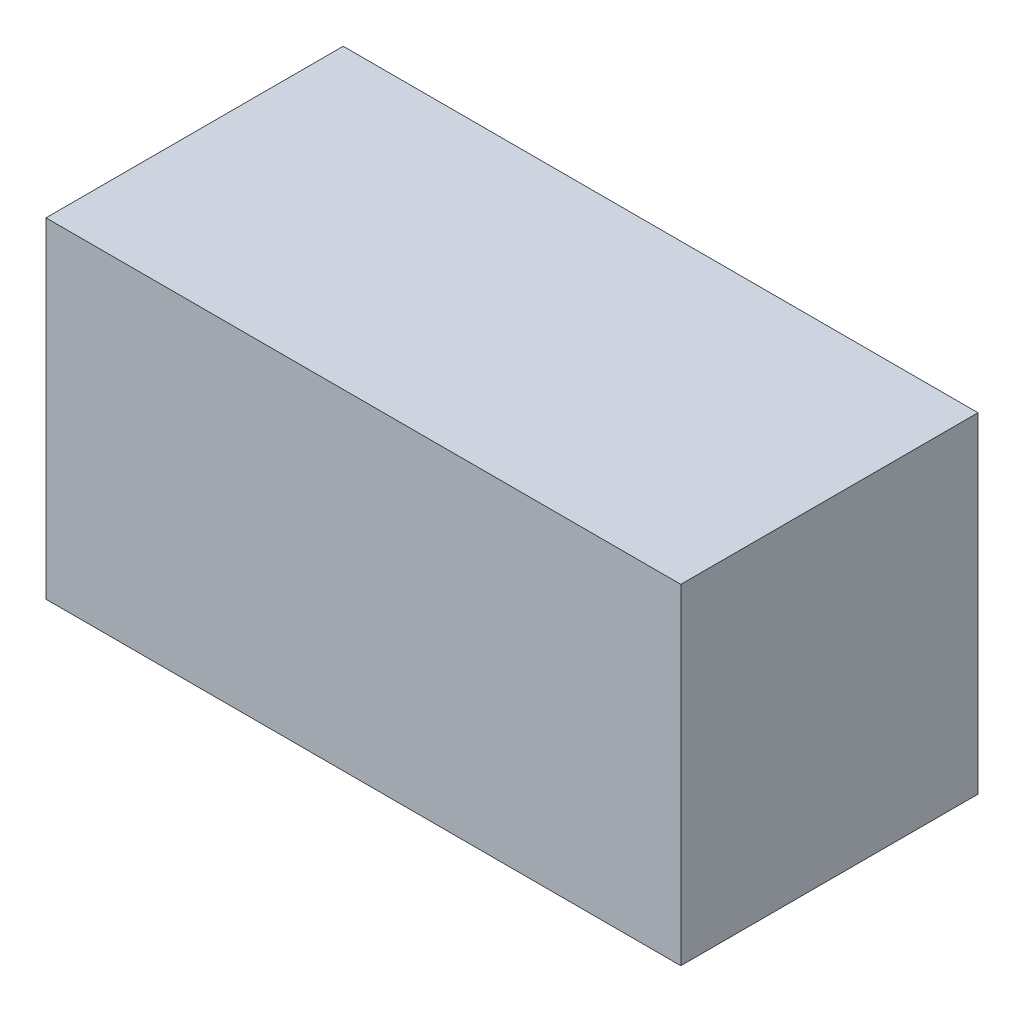
SolidWorks part; units mm, degrees
other "A"
other "B"
other "corpo 3"
other "C" parameters "Espessura"=2
material "AISI 1020"
ref_plane "Plano superior" through (0, 0, 0) normal (0, 0, 1) x (1, 0, 0)
ref_plane "Plano frontal" through (0, 0, 0) normal (0, 1, 0) x (1, 0, 0)
ref_plane "Plano direito" through (0, 0, 0) normal (1, 0, 0) x (0, 0, -1)
other "CAIXA"
ref_plane "Default Plane" through (78.1989, -63.755, 60) normal (0, 1, 0) x (1, 0, 0)
ref_plane "TOP" through (0, 0, 0) normal (0, 0, 1) x (1, 0, 0)
sketch "Esboço1" plane through (0, 0, 0) normal (0, 0, 1) x (1, 0, 0)
  line L1 (-78.1989, -63.755) -> (78.1989, -63.755)
  line L2 (-78.1989, -63.755) -> (-78.1989, 63.755)
  line L3 (-78.1989, 63.755) -> (78.1989, 63.755)
  line L4 (78.1989, -63.755) -> (78.1989, 63.755)
  line L5 (-78.1989, -63.755) -> (78.1989, 63.755) construction
  line L6 (-78.1989, 63.755) -> (78.1989, -63.755) construction
  circle A0 centre (0, 0) radius 15.125 construction
  point P0 (0, 0)
  dimension "D3" = 30.25
  dimension "D1" = 156.3979
  dimension "D2" = 127.51
extrude "Novo" add sketch "Esboço1" along normal blind 40
sketch "Esboço2" plane through (0, 0, 40) normal (0, 0, 1) x (1, 0, 0)
  line L0 (0, 0) -> (-78.1989, 0) construction
  line L1 (-78.1989, -63.755) -> (-53.5079, -63.755)
  line L2 (-78.1989, -63.755) -> (-78.1989, -43.755)
  line L3 (-78.1989, -43.755) -> (-53.5079, -43.755)
  line L4 (-53.5079, -63.755) -> (-53.5079, -43.755)
  line L5 (-78.1989, 63.755) -> (-78.1989, -63.755) construction
  line L6 (-78.1989, 43.755) -> (-53.5079, 43.755)
  line L7 (-53.5079, 63.755) -> (-53.5079, 43.755)
  line L8 (-78.1989, 63.755) -> (-53.5079, 63.755)
  line L9 (-78.1989, 63.755) -> (-78.1989, 43.755)
  line L10 (78.1989, 41.5261) -> (35.4788, 41.5261)
  line L11 (78.1989, -63.755) -> (35.4788, -63.755)
  line L12 (78.1989, -63.755) -> (78.1989, -41.5261)
  line L13 (78.1989, -41.5261) -> (35.4788, -41.5261)
  line L14 (35.4788, -63.755) -> (35.4788, -41.5261)
  line L15 (35.4788, 63.755) -> (35.4788, 41.5261)
  line L16 (78.1989, 63.755) -> (35.4788, 63.755)
  line L17 (78.1989, 63.755) -> (78.1989, 41.5261)
  dimension "D1" = 20
extrude "Ressalto-extrusão2" add sketch "Esboço2" along normal blind 20 separate body
delete or keep bodies "Corpo: A Mantido" [suppressed] type keep bodies bodies 111
delete or keep bodies "Corpo: C Mantido" type keep bodies bodies 114
delete or keep bodies "Corpo: B Mantido" [suppressed] type keep bodies bodies 114
